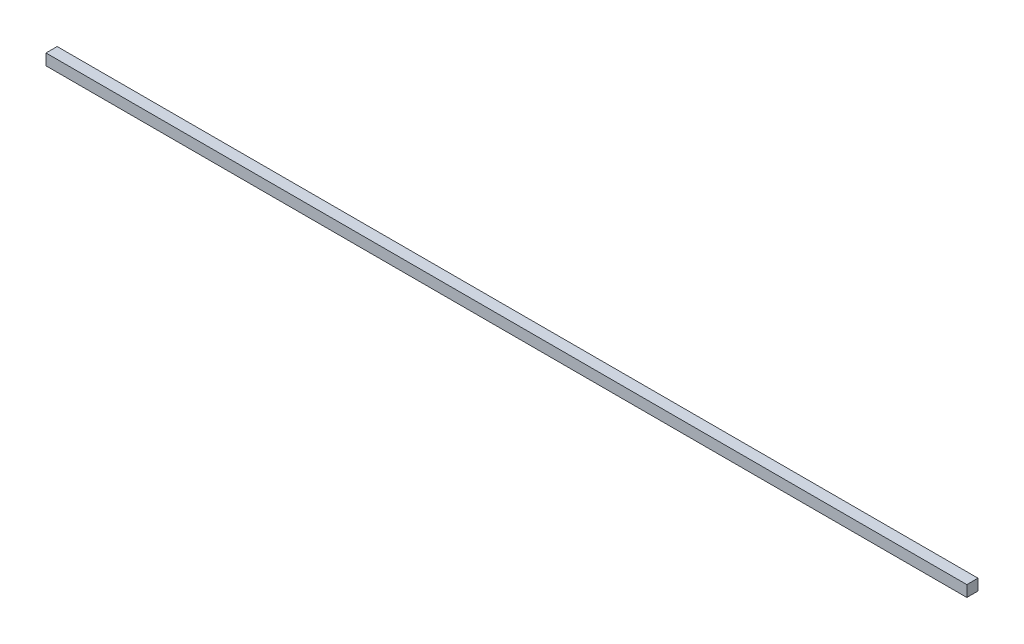
SolidWorks part; units mm, degrees
ref_plane "Front Plane" through (0, 0, 0) normal (0, 0, 1) x (1, 0, 0)
ref_plane "Top Plane" through (0, 0, 0) normal (0, 1, 0) x (1, 0, 0)
ref_plane "Right Plane" through (0, 0, 0) normal (1, 0, 0) x (0, 0, -1)
other "Configuration Table"
sketch "Sketch1" plane through (0, 0, 0) normal (0, 0, 1) x (1, 0, 0)
  line L1 (20, 462) -> (680, 462)
  line L2 (20, 462) -> (20, 470)
  line L3 (20, 470) -> (680, 470)
  line L4 (680, 462) -> (680, 470)
extrude "TOPPING_klape_alt1_pivot_mil_1" add sketch "Sketch1" along normal blind 8 from offset 22 separate body
